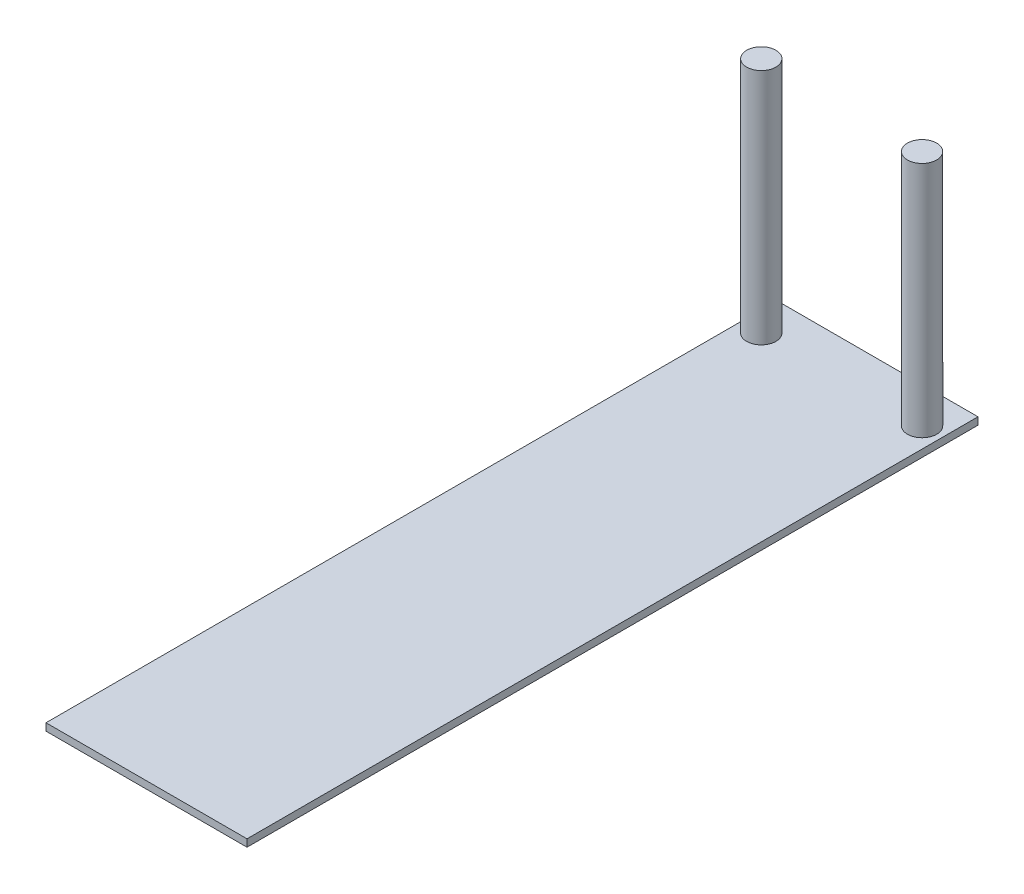
SolidWorks part; units mm, degrees
ref_plane "Front Plane" through (0, 0, 0) normal (0, 0, 1) x (1, 0, 0)
ref_plane "Top Plane" through (0, 0, 0) normal (0, 1, 0) x (1, 0, 0)
ref_plane "Right Plane" through (0, 0, 0) normal (1, 0, 0) x (0, 0, -1)
sketch "Sketch1" plane through (0, 0, 0) normal (0, 1, 0) x (1, 0, 0)
  line L0 (0, 0) -> (55.88, 0) construction
  line L2 (-6.985, -127) -> (62.865, -127)
  line L3 (-6.985, -127) -> (-6.985, 127)
  line L4 (-6.985, 127) -> (62.865, 127)
  line L5 (62.865, -127) -> (62.865, 127)
  line L6 (-6.985, -127) -> (62.865, 127) construction
  line L7 (-6.985, 127) -> (62.865, -127) construction
  point P5 (27.94, 0)
  dimension "D2" = 69.85
  dimension "D1" = 55.88
  dimension "D3" = 254
extrude "Boss-Extrude1" add sketch "Sketch1" along normal blind 2.54
sketch "Sketch2" plane through (0, 2.54, 0) normal (0, 1, 0) x (1, 0, 0)
  line L0 (27.94, 127) -> (27.94, -127) construction
  line L1 (62.865, 127) -> (-6.985, 127) construction
  line L2 (-6.985, -127) -> (62.865, -127) construction
  line L6 (0, 114.5611) -> (55.88, 114.5611) construction
  circle A0 centre (0, 114.5611) radius 5.08
  circle A1 centre (55.88, 114.5611) radius 5.08
  point P17 (0, 0)
  dimension "D1" = 55.88
  dimension "D2" = 10.16
  dimension "D3" = 10.16
  dimension "D4" = 27.94
extrude "Boss-Extrude2" add sketch "Sketch2" along normal blind 82.55
